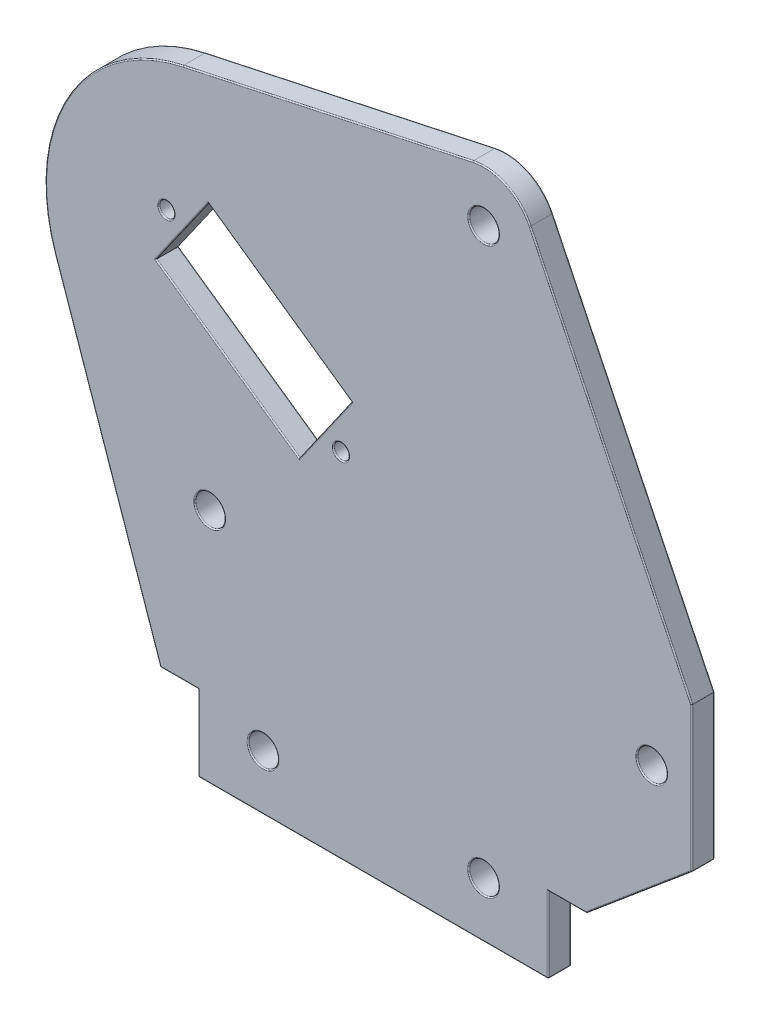
SolidWorks part; units mm, degrees
material "Plain Carbon Steel"
ref_plane "Front Plane" through (0, 0, 0) normal (0, 0, 1) x (1, 0, 0)
ref_plane "Top Plane" through (0, 0, 0) normal (0, 1, 0) x (1, 0, 0)
ref_plane "Right Plane" through (0, 0, 0) normal (1, 0, 0) x (0, 0, -1)
sketch "Sketch1" plane through (0, 0, 0) normal (0, 0, 1) x (1, 0, 0)
  line L0 (-23, 10) -> (-28, 10) construction
  line L1 (-23, 0) -> (23, 0) construction
  line L2 (-23, 0) -> (-23, 10) construction
  line L3 (23, 0) -> (23, 10) construction
  line L4 (23, 10) -> (28, 10) construction
  line L5 (28, 10) -> (41.85, 21.6215) construction
  line L6 (41.85, 21.6215) -> (41.85, 40.6215) construction
  line L7 (41.85, 40.6215) -> (20.6106, 84.4605) construction
  line L8 (-25.0297, 79.9436) -> (13.0723, 88.1382) construction
  line L9 (-28, 10) -> (-41.8438, 50.1182) construction
  line L10 (-23, 0) -> (23, 0)
  line L11 (23, 0) -> (23, 10)
  line L12 (23, 10) -> (28, 10)
  line L13 (28, 10) -> (41.85, 21.6215)
  line L14 (41.85, 21.6215) -> (41.85, 40.6215)
  line L15 (41.85, 40.6215) -> (20.6106, 84.4605)
  line L16 (-25.0297, 79.9436) -> (13.0723, 88.1382)
  line L17 (-28, 10) -> (-41.8438, 50.1182)
  line L18 (-23, 10) -> (-28, 10)
  line L19 (-23, 0) -> (-23, 10)
  line L20 (0, 0) -> (0, 17.4449) construction
  line L21 (-28.5764, 56.1065) -> (-21.6935, 65.9364)
  line L22 (-28.5764, 56.1065) -> (-9.7359, 42.9143)
  line L23 (-21.6935, 65.9364) -> (-2.853, 52.7441)
  line L24 (-9.7359, 42.9143) -> (-2.853, 52.7441)
  line L25 (-25.1349, 61.0215) -> (-6.2944, 47.8292) construction
  line L26 (-15.7147, 54.4253) -> (-19.1561, 49.5104) construction
  arc A0 (20.6106, 84.4605) -> (13.0723, 88.1382) centre (14.5, 81.5) ccw construction
  arc A1 (-25.0297, 79.9436) -> (-41.8438, 50.1182) centre (-20.22, 57.58) ccw construction
  arc A2 (20.6106, 84.4605) -> (13.0723, 88.1382) centre (14.5, 81.5) ccw
  arc A3 (-25.0297, 79.9436) -> (-41.8438, 50.1182) centre (-20.22, 57.58) ccw
  circle A4 centre (-27.1828, 62.4554) radius 1
  circle A5 centre (-4.2465, 46.3953) radius 1
  point P1 (-14.5, 7.25)
  point P2 (14.5, 7.25)
  point P5 (36.6, 31.1215)
  point P6 (-21.5, 31.1215)
  point P9 (-20.22, 57.58)
  point P10 (14.5, 81.5)
  point P26 (41.85, 31.1215)
  dimension "D8" = 2
  dimension "D1" = 5.25
  dimension "D2" = 7.25
  dimension "D3" = 21.5
  dimension "D4" = 23
  dimension "D5" = 12
  dimension "D6" = 35
  dimension "D7" = 6
  dimension "D9" = 2.5
extrude "Boss-Extrude1" add sketch "Sketch1" along normal blind 3
hole_wizard "M3.5 Clearance Hole1" positions "Sketch2" profile "Sketch3" hole size "M3.5" standard "ISO"
sketch "Sketch2" plane through (0, 0, 3) normal (0, 0, 1) x (1, 0, 0)
  point P0 (14.5, 81.5)
  point P3 (-21.5, 31.1215)
  point P6 (-14.5, 7.25)
  point P9 (14.5, 7.25)
  point P12 (36.6, 31.1215)
sketch "Sketch3" plane through (14.5, 81.5, 3) normal (1, 0, 0) x (0, -1, 0)
  line L0 (0, 0) -> (0, 4.1717)
  line L1 (0, 4.1717) -> (1.95, 3)
  line L2 (1.95, 3) -> (1.95, 0)
  line L5 (1.95, 0) -> (0, 0)
  line L10 (0, 4.1717) -> (-1.95, 3) construction
  line L11 (0, -6.35) -> (0, 107.95) construction
  dimension "Hole Dia." = 3.9
  dimension "Hole Depth" = 3
  dimension "Drill Angle" = 118
fillet "Fillet1" radius 0.15 52 edges at (16.45, 81.5, 3) (16.45, 81.5, 0) (-19.55, 31.1215, 3) (-19.55, 31.1215, 0) (-12.55, 7.25, 3) (-12.55, 7.25, 0) (16.45, 7.25, 3) (16.45, 7.25, 0) (38.55, 31.1215, 3) (38.55, 31.1215, 0) (-5.2465, 46.3953, 0) (-5.2465, 46.3953, 3) (-26.1828, 62.4554, 0) (-26.1828, 62.4554, 3) (-19.1561, 49.5104, 0) (-6.2944, 47.8292, 0) (-12.2732, 59.3402, 0) (-25.1349, 61.0215, 0) (-19.1561, 49.5104, 3) (-6.2944, 47.8292, 3) (-12.2732, 59.3402, 3) (-25.1349, 61.0215, 3) (-23, 5, 0) (0, 0, 0) (23, 5, 0) (25.5, 10, 0) (34.925, 15.8108, 0) (41.85, 31.1215, 0) (31.2303, 62.541, 0) (17.4772, 87.6025, 0) (-5.9787, 84.0409, 0) (-40.1467, 68.8136, 0) (-34.9219, 30.0591, 0) (-25.5, 10, 0) (-23, 5, 3) (0, 0, 3) (23, 5, 3) (25.5, 10, 3) (34.925, 15.8108, 3) (41.85, 31.1215, 3) (31.2303, 62.541, 3) (17.4772, 87.6025, 3) (-5.9787, 84.0409, 3) (-40.1467, 68.8136, 3) (-34.9219, 30.0591, 3) (-25.5, 10, 3) (-28, 10, 1.5) (41.85, 40.6215, 1.5) (41.85, 21.6215, 1.5) (28, 10, 1.5) (-23, 0, 1.5) (23, 0, 1.5)
sketch "Sketch4" plane through (0, 0, 0) normal (0, 0, -1) x (-1, 0, 0)
  line L0 (-25.7911, 4.75) -> (26.4627, 4.75)
  line L2 (26.4627, 4.75) -> (25.6997, -7.1496)
  line L3 (25.6997, -7.1496) -> (-24.1807, -5.3375)
  line L4 (-24.1807, -5.3375) -> (-25.7911, 4.75)
  line L6 (22.85, 0) -> (-22.85, 0) construction
  dimension "D1" = 4.75
extrude "Cut-Extrude1" [suppressed] cut sketch "Sketch4" against normal blind 10
